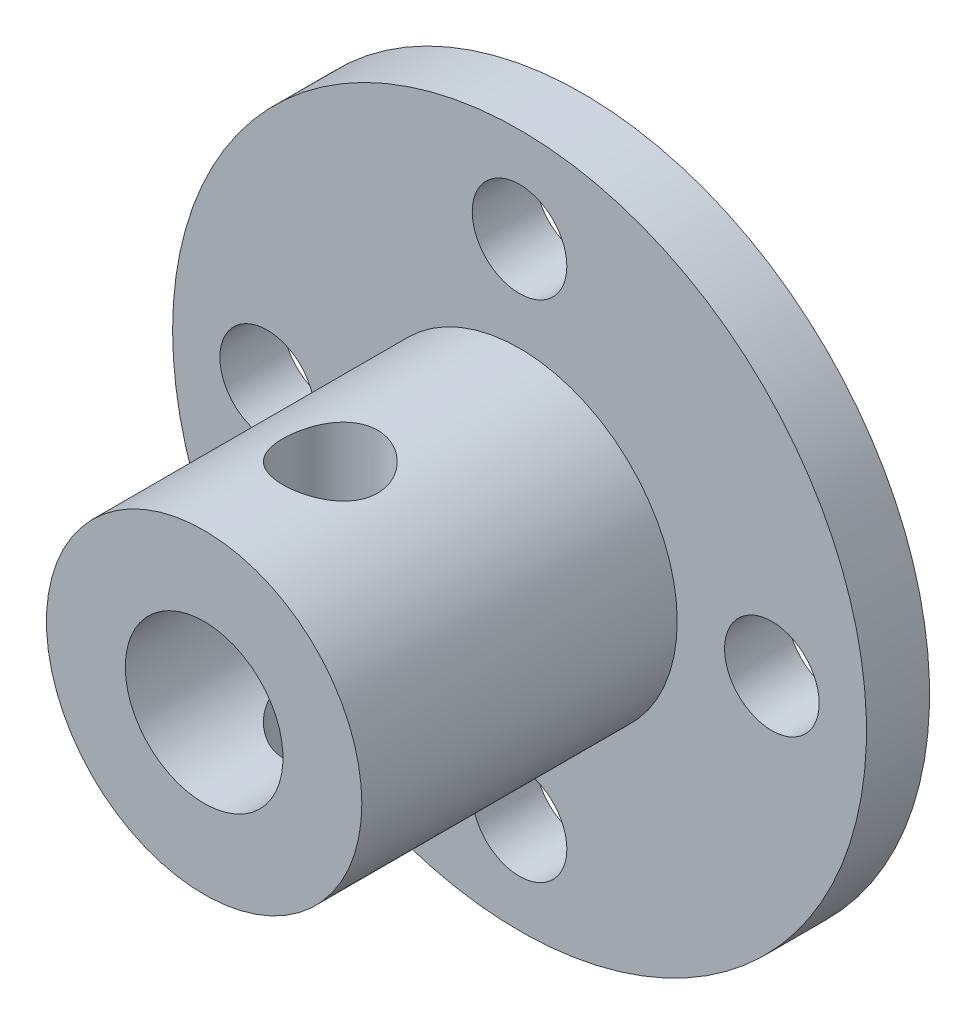
SolidWorks part; units mm, degrees
material "Material"
ref_plane "Front Plane" through (0, 0, 0) normal (0, 0, 1) x (1, 0, 0)
ref_plane "Top Plane" through (0, 0, 0) normal (0, 1, 0) x (1, 0, 0)
ref_plane "Right Plane" through (0, 0, 0) normal (1, 0, 0) x (0, 0, -1)
ref_plane "Plane1" through (0, 0, 0) normal (0, -1, 0) x (1, 0, 0)
sketch "Sketch1" plane through (0, 0, 0) normal (0, -1, 0) x (1, 0, 0)
  line L0 (11, 2) -> (0, 2)
  line L1 (0, 2) -> (0, 0)
  line L2 (0, 0) -> (11, 0)
  line L3 (11, 0) -> (11, 2)
  line L4 (0, 2) -> (0, 0) construction
revolve "Revolve1" add sketch "Sketch1" angle 360 about L4
sketch "Sketch2" plane through (0, 0, 2) normal (0, 0, 1) x (1, 0, 0)
  circle A0 centre (0, 0) radius 5
extrude "Boss-Extrude1" add sketch "Sketch2" along normal blind 10
hole_wizard "Ø3.0 (3) Diameter Hole1" positions "Sketch4" profile "Sketch3" hole size "Ø3.0" standard "ANSI Metric"
sketch "Sketch4" plane through (0, 0, 0) normal (0, 0, -1) x (-1, 0, 0)
  point P0 (0, 8)
  point P1 (-8, 0)
  point P2 (0, -8)
  point P3 (8, 0)
sketch "Sketch3" plane through (0, 8, 0) normal (1, 0, 0) x (0, 1, 0)
  line L0 (0, 0) -> (0, 12)
  line L1 (0, 12) -> (1.5, 12)
  line L2 (1.5, 12) -> (1.5, 0)
  line L5 (1.5, 0) -> (0, 0)
  line L11 (0, -6.35) -> (0, 107.95) construction
  dimension "Thru Hole Dia." = 3
  dimension "Thru Hole Depth" = 12
hole_wizard "Ø5.0 (5) Diameter Hole1" positions "Sketch6" profile "Sketch5" hole size "Ø5.0" standard "ANSI Metric"
sketch "Sketch6" plane through (0, 0, 0) normal (0, 0, -1) x (-1, 0, 0)
  point P0 (0, 0)
sketch "Sketch5" plane through (0, 0, 0) normal (1, 0, 0) x (0, 1, 0)
  line L0 (0, 0) -> (0, 12)
  line L1 (0, 12) -> (2.5, 12)
  line L2 (2.5, 12) -> (2.5, 0)
  line L5 (2.5, 0) -> (0, 0)
  line L11 (0, -6.35) -> (0, 107.95) construction
  dimension "Thru Hole Dia." = 5
  dimension "Thru Hole Depth" = 12
hole_wizard "Ø3.0 (3) Diameter Hole2" positions "3DSketch1" profile "Sketch7" hole size "Ø3.0" standard "ANSI Metric"
sketch3d "3DSketch1"
  point P0 (0, 5, 8)
sketch "Sketch7" plane through (0, 5, 8) normal (1, 0, 0) x (0, 0, 1)
  line L0 (0, 0) -> (0, 13)
  line L1 (0, 13) -> (1.5, 13)
  line L2 (1.5, 13) -> (1.5, 0)
  line L5 (1.5, 0) -> (0, 0)
  line L10 (0, 13) -> (-1.5, 13) construction
  line L11 (0, -6.35) -> (0, 107.95) construction
  dimension "Hole Dia." = 3
  dimension "Hole Depth" = 13
  dimension "Drill Angle" = 180
